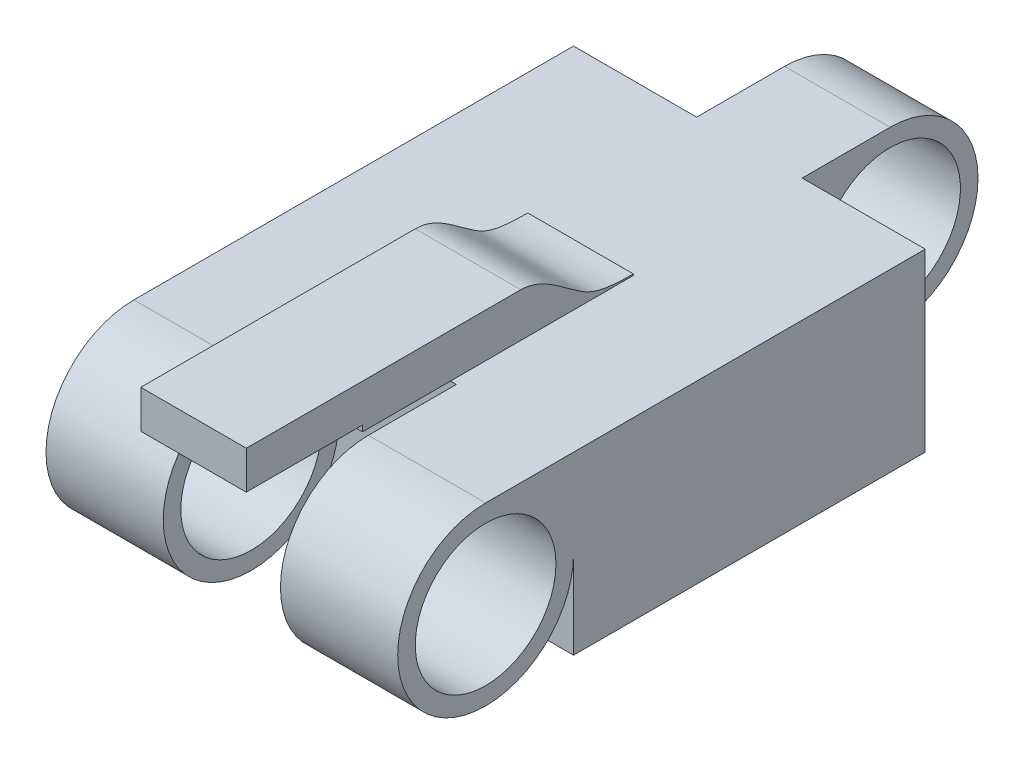
SolidWorks part; units mm, degrees
ref_plane "Front Plane" through (0, 0, 0) normal (0, 0, 1) x (1, 0, 0)
ref_plane "Top Plane" through (0, 0, 0) normal (0, 1, 0) x (1, 0, 0)
ref_plane "Right Plane" through (0, 0, 0) normal (1, 0, 0) x (0, 0, -1)
sketch "Sketch2" plane through (0, 0, 0) normal (1, 0, 0) x (0, 0, -1)
  line L1 (0, 0) -> (10, 0)
  line L2 (0, 0) -> (0, 5)
  line L3 (0, 5) -> (10, 5)
  line L4 (10, 0) -> (10, 5)
  dimension "D1" = 10
  dimension "D2" = 5
extrude "Boss-Extrude1" add sketch "Sketch2" along normal blind 10
sketch "Sketch3" plane through (0, 0, 0) normal (-1, 0, 0) x (0, 0, 1)
  line L0 (0, 2.5) -> (2.5, 2.5) construction
  line L1 (0, 5) -> (0, 0) construction
  line L2 (2.5, 5) -> (0, 5)
  line L3 (0, 5) -> (0, 2.5)
  arc A0 (0, 2.5) -> (2.5, 5) centre (2.5, 2.5) ccw
  circle A1 centre (2.5, 2.5) radius 2
  dimension "D1" = 4
extrude "Boss-Extrude2" add sketch "Sketch3" against normal blind 3.3333
sketch "Sketch4" plane through (10, 0, 0) normal (1, 0, 0) x (0, 0, -1)
  line L0 (0, 2.5) -> (-2.5, 2.5) construction
  line L1 (0, 5) -> (0, 0) construction
  line L2 (-2.5, 5) -> (0, 5)
  line L3 (0, 5) -> (0, 2.5)
  circle A0 centre (-2.5, 2.5) radius 2
  arc A1 (-2.5, 5) -> (0, 2.5) centre (-2.5, 2.5) ccw
extrude "Boss-Extrude3" add sketch "Sketch4" against normal blind 3.3333
sketch "Sketch5" plane through (0, 5, 0) normal (0, 1, 0) x (1, 0, 0)
  line L0 (0, 10) -> (5, 10) construction
  line L1 (10, 10) -> (0, 10) construction
  line L2 (5, 10) -> (5, 6.9018) construction
ref_plane "Plane1" through (5, 0, 0) normal (-1, 0, 0) x (0, 0, 1)
sketch "Sketch6" plane through (5, 0, 0) normal (-1, 0, 0) x (0, 0, 1)
  line L0 (-10, 5) -> (-10, 2.5) construction
  line L1 (-10, 0) -> (-10, 5) construction
  line L2 (-10, 2.5) -> (-12.5, 2.5) construction
  line L3 (-12.5, 5) -> (-10, 5)
  line L4 (-10, 5) -> (-10, 2.5)
  arc A0 (-12.5, 5) -> (-10, 2.5) centre (-12.5, 2.5) ccw
  circle A1 centre (-12.5, 2.5) radius 2
extrude "Boss-Extrude4" add sketch "Sketch6" along normal blind 1.5 and the other way blind 1.5
sketch "Sketch8" plane through (5, 0, 0) normal (-1, 0, 0) x (0, 0, 1)
  line L0 (0, 2.5) -> (0, 5) construction
  line L1 (0, 5) -> (-2, 5)
  line L2 (-10, 5) -> (2.5, 5) construction
  line L4 (-2, 6.25) -> (8, 6.25)
  line L5 (8, 6.25) -> (8, 5)
  line L6 (8, 5) -> (0, 5)
  line L7 (-2, 5) -> (-5.2, 5)
  line L8 (-5.2, 5) -> (-5.2, 5.04)
  spline S0 degree 3 poles (-2, 6.25) (-2.4949, 6.25) (-3.0572, 5.8103) (-3.8665, 5.2415) (-4.161, 5.04) (-5.2, 5.04) knots 0 0 0 0 0.415213 0.515213 1 1 1 1
  point P13 (-3.423, 5.5535)
  dimension "D1" = 10
  dimension "D2" = 8
  dimension "D3" = 1.25
extrude "Boss-Extrude5" add sketch "Sketch8" along normal blind 1.5 and the other way blind 1.5
sketch "Sketch9" plane through (3.5, 0, 0) normal (-1, 0, 0) x (0, 0, 1)
  line L0 (8, 6.25) -> (5.8053, 6.25)
  line L1 (8, 6.25) -> (-2, 6.25) construction
  line L2 (5.8053, 6.25) -> (5.8053, 5.1672)
  line L4 (2.5, 5) -> (2.5, 5.1672)
  line L5 (2.5, 5.1672) -> (5.8053, 5.1672)
  line L6 (2.5, 5) -> (8, 5)
  line L7 (8, 5) -> (8, 6.25)
extrude "Cut-Extrude1" cut sketch "Sketch9" against normal through all
